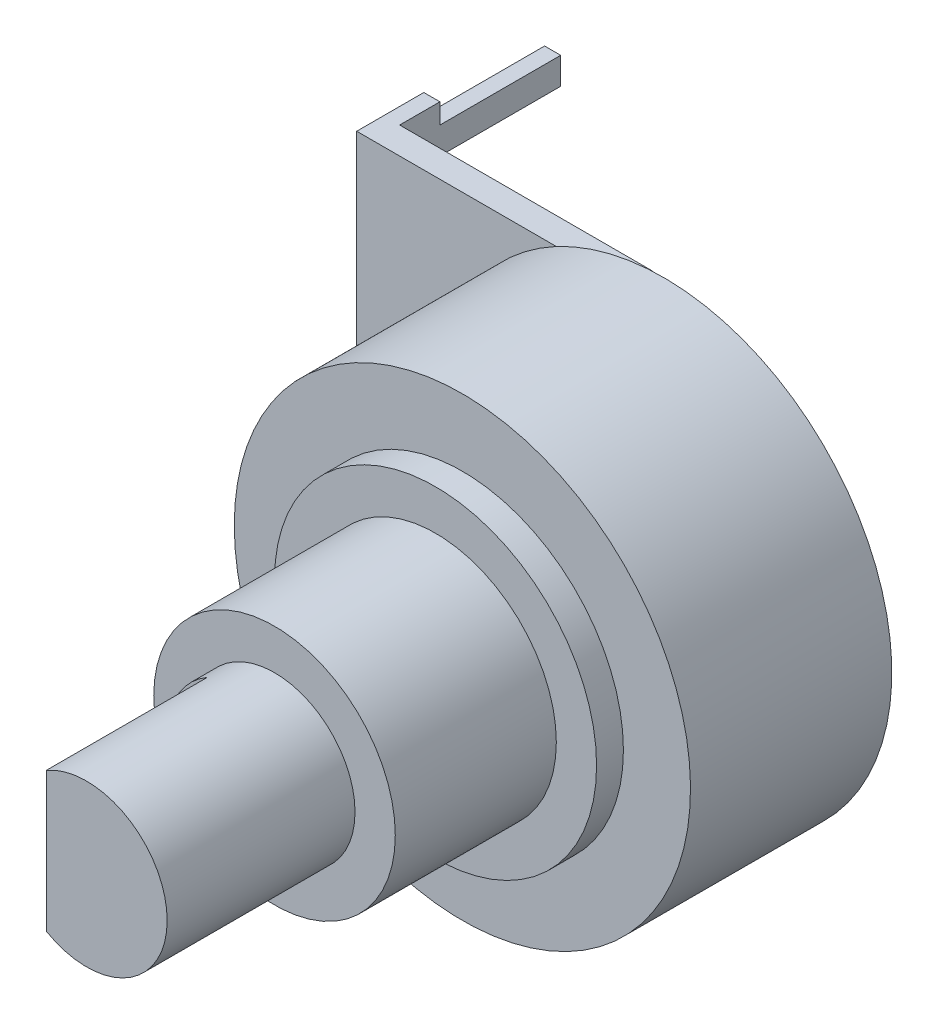
SolidWorks part; units mm, degrees
ref_plane "Спереди" through (0, 0, 0) normal (0, 0, 1) x (1, 0, 0)
ref_plane "Сверху" through (0, 0, 0) normal (0, 1, 0) x (1, 0, 0)
ref_plane "Справа" through (0, 0, 0) normal (1, 0, 0) x (0, 0, -1)
other "Configuration Table"
sketch "Эскиз1" plane through (0, 0, 0) normal (0, 0, 1) x (1, 0, 0)
  circle A0 centre (0, 0) radius 4.5
  dimension "D1" = 9
extrude "Бобышка-Вытянуть1" add sketch "Эскиз1" along normal blind 6
sketch "Эскиз2" plane through (0, 0, 6) normal (0, 0, 1) x (1, 0, 0)
  circle A0 centre (0, 0) radius 3
  dimension "D1" = 6
extrude "Бобышка-Вытянуть2" add sketch "Эскиз2" along normal blind 7
sketch "Эскиз3" plane through (0, 0, 13) normal (0, 0, 1) x (1, 0, 0)
  line L1 (-5.2683, 3.6149) -> (-1.5, 3.6149)
  line L2 (-5.2683, 3.6149) -> (-5.2683, -2.903)
  line L3 (-5.2683, -2.903) -> (-1.5, -2.903)
  line L4 (-1.5, 3.6149) -> (-1.5, -2.903)
  dimension "D1" = 1.5
extrude "Вырез-Вытянуть1" cut sketch "Эскиз3" against normal blind 6
sketch "Эскиз4" plane through (0, 0, 0) normal (0, 0, -1) x (-1, 0, 0)
  circle A0 centre (0, 0) radius 6
  dimension "D1" = 12
extrude "Бобышка-Вытянуть3" add sketch "Эскиз4" along normal blind 1
sketch "Эскиз5" plane through (0, 0, -1) normal (0, 0, -1) x (-1, 0, 0)
  circle A0 centre (0, 0) radius 8.5
  dimension "D1" = 17
extrude "Бобышка-Вытянуть4" add sketch "Эскиз5" along normal blind 7.5
sketch "Эскиз6" plane through (0, 0, -8.5) normal (0, 0, -1) x (-1, 0, 0)
  line L1 (1.4375, 7.5) -> (11.4375, 7.5)
  line L2 (1.4375, 7.5) -> (1.4375, -7.5)
  line L3 (1.4375, -7.5) -> (11.4375, -7.5)
  line L4 (11.4375, 7.5) -> (11.4375, -7.5)
  point P4 (1.4375, 0)
  dimension "D1" = 0
  dimension "D2" = 15
  dimension "D3" = 10
extrude "Бобышка-Вытянуть5" add sketch "Эскиз6" along normal blind 1
sketch "Эскиз7" plane through (0, 0, -9.5) normal (0, 0, -1) x (-1, 0, 0)
  line L0 (11.4375, 7.5) -> (1.4375, 7.5) construction
  line L1 (11.4375, 7.5) -> (10.8375, 7.5)
  line L2 (11.4375, 7.5) -> (11.4375, 5)
  line L3 (11.4375, 5) -> (10.8375, 5)
  line L4 (10.8375, 7.5) -> (10.8375, 5)
  line L5 (11.4375, -7.5) -> (11.4375, 7.5) construction
  line L6 (1.4375, -7.5) -> (11.4375, -7.5) construction
  line L7 (11.4375, 1.25) -> (10.8375, 1.25)
  line L8 (11.4375, 1.25) -> (11.4375, -1.25)
  line L9 (11.4375, -1.25) -> (10.8375, -1.25)
  line L10 (10.8375, 1.25) -> (10.8375, -1.25)
  line L11 (11.4375, -5) -> (10.8375, -5)
  line L12 (11.4375, -5) -> (11.4375, -7.5)
  line L13 (11.4375, -7.5) -> (10.8375, -7.5)
  line L14 (10.8375, -5) -> (10.8375, -7.5)
  point P18 (10.8375, 0)
  dimension "D1" = 0
  dimension "D2" = 2.5
  dimension "D3" = 0.6
extrude "Бобышка-Вытянуть6" add sketch "Эскиз7" along normal blind 6
sketch "Эскиз8" plane through (-11.4375, 0, 0) normal (-1, 0, 0) x (0, 0, 1)
  line L0 (-15.5, -5) -> (-9.5, -5) construction
  line L1 (-15.5, 7.5) -> (-11, 7.5)
  line L2 (-15.5, 7.5) -> (-15.5, 6.75)
  line L3 (-15.5, 6.75) -> (-11, 6.75)
  line L4 (-11, 7.5) -> (-11, 6.75)
  line L5 (-15.5, 5) -> (-11, 5)
  line L6 (-15.5, 5) -> (-15.5, 5.75)
  line L7 (-15.5, 5.75) -> (-11, 5.75)
  line L8 (-11, 5) -> (-11, 5.75)
  line L9 (-15.5, 1.25) -> (-11, 1.25)
  line L10 (-15.5, 1.25) -> (-15.5, 0.5)
  line L11 (-15.5, 0.5) -> (-11, 0.5)
  line L12 (-11, 1.25) -> (-11, 0.5)
  line L13 (-15.5, -1.25) -> (-11, -1.25)
  line L14 (-15.5, -1.25) -> (-15.5, -0.5)
  line L15 (-15.5, -0.5) -> (-11, -0.5)
  line L16 (-11, -1.25) -> (-11, -0.5)
  line L17 (-15.5, -5) -> (-11, -5)
  line L18 (-15.5, -5) -> (-15.5, -5.75)
  line L19 (-15.5, -5.75) -> (-11, -5.75)
  line L20 (-11, -5) -> (-11, -5.75)
  line L21 (-15.5, -7.5) -> (-15.5, -5) construction
  line L23 (-15.5, -7.5) -> (-11, -7.5)
  line L24 (-15.5, -7.5) -> (-15.5, -6.75)
  line L25 (-15.5, -6.75) -> (-11, -6.75)
  line L26 (-11, -7.5) -> (-11, -6.75)
  dimension "D1" = 4.5
  dimension "D2" = 1
extrude "Вырез-Вытянуть2" cut sketch "Эскиз8" against normal through all
